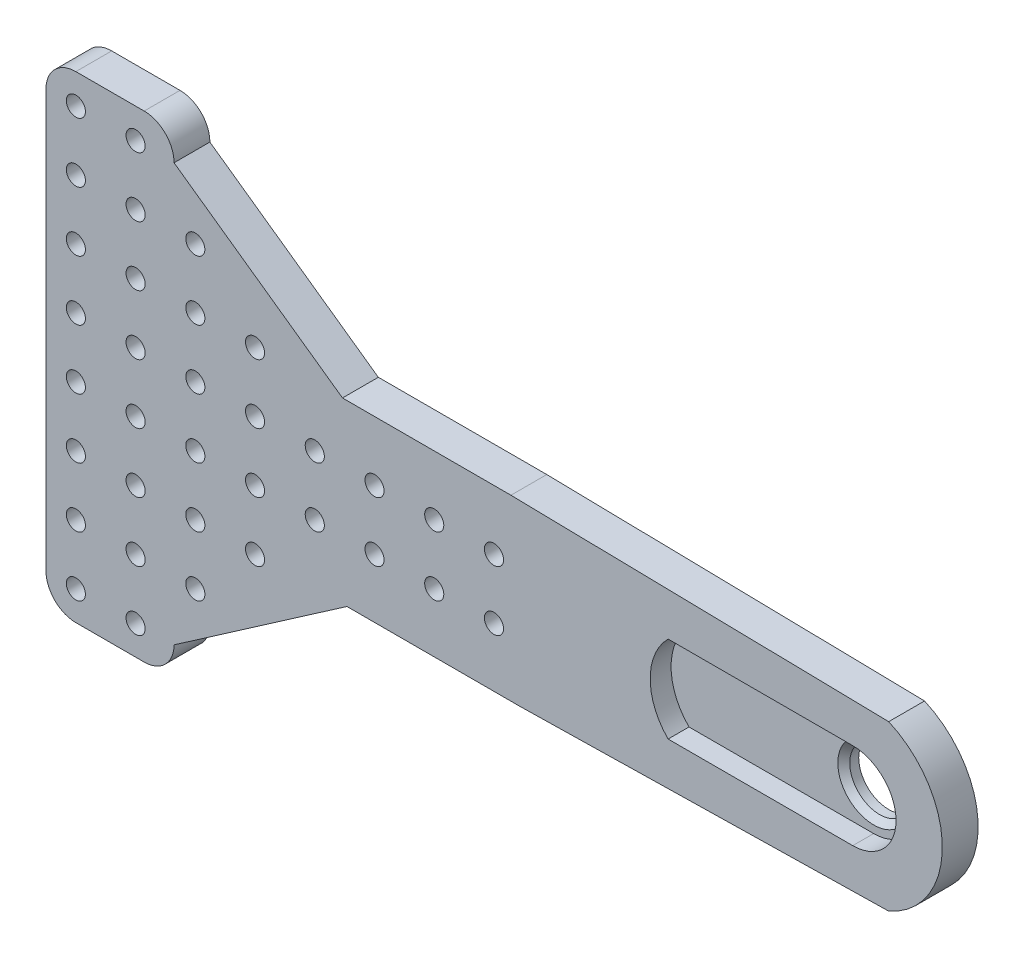
SolidWorks part; units mm, degrees
ref_plane "Ön Düzlem" through (0, 0, 0) normal (0, 0, 1) x (1, 0, 0)
ref_plane "Üst Düzlem" through (0, 0, 0) normal (0, 1, 0) x (1, 0, 0)
ref_plane "Sağ Düzlem" through (0, 0, 0) normal (1, 0, 0) x (0, 0, -1)
sketch "Çizim1" plane through (0, 0, 0) normal (0, 0, 1) x (1, 0, 0)
  line L0 (-35.653, 0) -> (24.347, 0) construction
  line L1 (-35.653, 15) -> (24.347, 15)
  line L2 (-35.653, -15) -> (24.347, -15)
  arc A0 (-35.653, 15) -> (-35.653, -15) centre (-35.653, 0) ccw
  arc A1 (24.347, -15) -> (24.347, 15) centre (24.347, 0) ccw
  point P3 (-5.653, 0)
  dimension "D1" = 15
  dimension "D2" = 60
extrude "Yükseklik-Ekstrüzyon1" add sketch "Çizim1" along normal blind 4
sketch "Çizim2" plane through (0, 0, 4) normal (0, 0, 1) x (1, 0, 0)
  line L0 (-35.653, 15) -> (-33.2438, 4.5907)
  line L1 (-33.2438, 4.5907) -> (11.7295, 15)
  line L2 (24.347, 15) -> (-35.653, 15) construction
  line L3 (11.7295, 15) -> (11.5926, 15.5911)
  line L4 (11.5926, 15.5911) -> (9.0388, 15)
  line L5 (9.0388, 15) -> (9.2838, 13.9414)
  line L6 (9.2838, 13.9414) -> (13.8573, 15)
  line L7 (13.8573, 15) -> (14.1023, 13.9414)
  line L8 (14.1023, 13.9414) -> (18.6759, 15)
  line L9 (18.6759, 15) -> (17.1385, 21.6425)
  line L10 (17.1385, 21.6425) -> (-11.5602, 15)
  line L11 (-11.5602, 15) -> (-9.1509, 4.5907)
  line L12 (-9.1509, 4.5907) -> (35.8223, 15)
  line L13 (-35.653, 0) -> (-9.6355, 0) construction
  line L14 (-9.1509, -4.5907) -> (35.8223, -15)
  line L15 (-35.653, -15) -> (24.347, -15)
  line L16 (24.347, 15) -> (-35.653, 15)
  line L17 (-35.653, -15) -> (24.347, -15)
  line L18 (35.8223, 15) -> (-35.653, 15)
  line L19 (-11.5602, -15) -> (-9.1509, -4.5907)
  line L20 (17.1385, -21.6425) -> (-11.5602, -15)
  line L21 (18.6759, -15) -> (17.1385, -21.6425)
  line L22 (14.1023, -13.9414) -> (18.6759, -15)
  line L23 (13.8573, -15) -> (14.1023, -13.9414)
  line L24 (9.2838, -13.9414) -> (13.8573, -15)
  line L25 (9.0388, -15) -> (9.2838, -13.9414)
  line L26 (11.5926, -15.5911) -> (9.0388, -15)
  line L27 (11.7295, -15) -> (11.5926, -15.5911)
  line L28 (-33.2438, -4.5907) -> (11.7295, -15)
  line L29 (-35.653, -15) -> (-33.2438, -4.5907)
  arc A2 (-35.653, 15) -> (-35.653, -15) centre (-35.653, 0) ccw
  arc A3 (24.347, -15) -> (24.347, 15) centre (24.347, 0) ccw
  arc A5 (24.347, -15) -> (24.347, 15) centre (24.347, 0) ccw
  line M7 (-35.653, -15) -> (24.347, -15)
  line M9 (24.347, 15) -> (-35.653, 15)
  dimension "D1" = 0
extrude "Kes-Ekstrüzyon1" cut sketch "Çizim2" against normal blind 4 contours L0 L1 M9 | L3 L4 M9 | L5 L6 M9 | L7 L8 M9 | L9 L10 M9 | L11 L12 M9 | L19 L17 L14 | L21 L17 L20 | L23 L17 L22 | L25 L17 L24 | L27 L17 L26 | L29 L28 M7
sketch "Çizim3" plane through (0, 0, 4) normal (0, 0, 1) x (1, 0, 0)
  circle A0 centre (24.347, 0) radius 5
  dimension "D1" = 10
extrude "Kes-Ekstrüzyon2" cut sketch "Çizim3" against normal blind 4
sketch "Çizim5" plane through (0, 0, 4) normal (0, 0, 1) x (1, 0, 0)
  line L3 (-10.376, -9.8836) -> (-11.5602, -15)
  line L4 (-11.5602, -15) -> (11.7295, -15)
  line L5 (11.7295, -15) -> (-10.376, -9.8836)
  line L6 (-10.376, -9.8836) -> (-11.5602, -15)
  line L7 (-11.5602, -15) -> (11.7295, -15)
  line L8 (11.7295, -15) -> (-10.376, -9.8836)
  line L9 (-11.5602, 15) -> (-10.376, 9.8836)
  line L10 (-10.376, 9.8836) -> (11.7295, 15)
  line L11 (11.7295, 15) -> (-11.5602, 15)
  line L12 (-11.5602, 15) -> (-10.376, 9.8836)
  line L13 (-10.376, 9.8836) -> (11.7295, 15)
  line L14 (11.7295, 15) -> (-11.5602, 15)
  dimension "D1" = 0
  dimension "D2" = 0
extrude "Kes-Ekstrüzyon3" cut sketch "Çizim5" against normal blind 4
sketch "Çizim10" plane through (0, 0, 4) normal (0, 0, 1) x (1, 0, 0)
  line L0 (23.5737, 7.2086) -> (5.173, 5.2349)
  line L1 (22.9992, -7.1236) -> (5.2458, -3.7648)
  circle A0 centre (24.347, 0) radius 7.25
  arc A1 (5.173, 5.2349) -> (5.2458, -3.7648) centre (5.2094, 0.7351) ccw
  circle M2 centre (24.347, 0) radius 5
  dimension "D1" = 14.5
  dimension "D2" = 9
extrude "Kes-Ekstrüzyon4" cut sketch "Çizim10" against normal blind 3.5 contours L0 A1 L1 A0 | A0 M2
sketch "Çizim11" plane through (0, 0, 0) normal (0, 0, -1) x (-1, 0, 0)
  line L8 (33.2438, -4.5907) -> (35.653, -15)
  line L9 (35.653, 15) -> (33.2438, 4.5907)
  line L10 (33.2438, 4.5907) -> (10.376, 9.8836)
  line L11 (10.376, 9.8836) -> (9.1509, 4.5907)
  line L12 (9.1509, 4.5907) -> (-30.3694, 13.7379)
  line L13 (-30.3694, -13.7379) -> (9.1509, -4.5907)
  line L14 (9.1509, -4.5907) -> (10.376, -9.8836)
  line L15 (10.376, -9.8836) -> (33.2438, -4.5907)
  line L16 (33.2438, -4.5907) -> (35.653, -15)
  line L17 (35.653, 15) -> (33.2438, 4.5907)
  line L18 (33.2438, 4.5907) -> (10.376, 9.8836)
  line L19 (10.376, 9.8836) -> (9.1509, 4.5907)
  line L20 (9.1509, 4.5907) -> (-30.3694, 13.7379)
  line L21 (-30.3694, -13.7379) -> (9.1509, -4.5907)
  line L22 (9.1509, -4.5907) -> (10.376, -9.8836)
  line L23 (10.376, -9.8836) -> (33.2438, -4.5907)
  circle A0 centre (-24.347, 0) radius 5 construction
  circle A1 centre (-24.347, 0) radius 5
  arc A2 (35.653, -15) -> (35.653, 15) centre (35.653, 0) ccw
  arc A3 (-30.3694, 13.7379) -> (-30.3694, -13.7379) centre (-24.347, 0) ccw
  arc A4 (35.653, -15) -> (35.653, 15) centre (35.653, 0) ccw
  arc A5 (-30.3694, 13.7379) -> (-30.3694, -13.7379) centre (-24.347, 0) ccw
  dimension "D1" = 0
extrude "Yükseklik-Ekstrüzyon3" add sketch "Çizim11" along normal blind 2
chamfer "Pah2" distance 1 angle 45 1 edges at (29.347, 0, 0.5)
sketch "Çizim12" plane through (0, 0, 4) normal (0, 0, 1) x (1, 0, 0)
  line L0 (-35.653, 15) -> (30.3694, 13.7379)
  line L1 (30.3694, -13.7379) -> (-35.653, -15)
  line L10 (-35.653, -15) -> (-33.2438, -4.5907)
  line L11 (-33.2438, -4.5907) -> (-10.376, -9.8836)
  line L12 (-10.376, -9.8836) -> (-9.1509, -4.5907)
  line L13 (-9.1509, -4.5907) -> (30.3694, -13.7379)
  line L14 (30.3694, 13.7379) -> (-9.1509, 4.5907)
  line L15 (-9.1509, 4.5907) -> (-10.376, 9.8836)
  line L16 (-10.376, 9.8836) -> (-33.2438, 4.5907)
  line L17 (-33.2438, 4.5907) -> (-35.653, 15)
  line L18 (-35.653, -15) -> (-33.2438, -4.5907)
  line L19 (-33.2438, -4.5907) -> (-10.376, -9.8836)
  line L20 (-10.376, -9.8836) -> (-9.1509, -4.5907)
  line L21 (-9.1509, -4.5907) -> (30.3694, -13.7379)
  line L22 (30.3694, 13.7379) -> (-9.1509, 4.5907)
  line L23 (-9.1509, 4.5907) -> (-10.376, 9.8836)
  line L24 (-10.376, 9.8836) -> (-33.2438, 4.5907)
  line L25 (-33.2438, 4.5907) -> (-35.653, 15)
  arc A2 (-35.653, 15) -> (-35.653, -15) centre (-35.653, 0) ccw
  arc A3 (30.3694, -13.7379) -> (30.3694, 13.7379) centre (24.347, 0) ccw
  arc A4 (-35.653, 15) -> (-35.653, -15) centre (-35.653, 0) ccw
  arc A5 (30.3694, -13.7379) -> (30.3694, 13.7379) centre (24.347, 0) ccw
  line M16 (-35.653, -15) -> (-33.2438, -4.5907)
  line M17 (-33.2438, -4.5907) -> (-10.376, -9.8836)
  line M18 (-10.376, -9.8836) -> (-9.1509, -4.5907)
  line M19 (-9.1509, -4.5907) -> (30.3694, -13.7379)
  line M21 (30.3694, 13.7379) -> (-9.1509, 4.5907)
  line M22 (-9.1509, 4.5907) -> (-10.376, 9.8836)
  line M23 (-10.376, 9.8836) -> (-33.2438, 4.5907)
  line M24 (-33.2438, 4.5907) -> (-35.653, 15)
  dimension "D1" = 0
extrude "Yükseklik-Ekstrüzyon4" add sketch "Çizim12" against normal up to surface (6 mm away) contours L0 M24 M23 M22 M21 | L1 M19 M18 M17 M16 up to face at (-12.2131, 0, -2)
sketch "Çizim13" plane through (0, 0, 4) normal (0, 0, 1) x (1, 0, 0)
  line L0 (-32.8787, 14.947) -> (-32.5322, 34.86)
  line L1 (-35.653, 15) -> (30.3694, 13.7379) construction
  line L2 (-37.5315, 39.947) -> (-45.7205, 39.947)
  line L3 (-50.7205, 34.947) -> (-50.7205, -34.9515)
  line L4 (-45.7205, -39.9515) -> (-37.8787, -39.9515)
  line L5 (-32.8787, -34.9515) -> (-32.8787, 14.947)
  line L6 (30.3694, -13.7379) -> (-35.653, -15) construction
  arc A0 (-50.7205, -34.9515) -> (-45.7205, -39.9515) centre (-45.7205, -34.9515) ccw
  arc A1 (-37.8787, -39.9515) -> (-32.8787, -34.9515) centre (-37.8787, -34.9515) ccw
  arc A2 (-32.5322, 34.86) -> (-37.5315, 39.947) centre (-37.5315, 34.947) ccw
  arc A3 (-45.7205, 39.947) -> (-50.7205, 34.947) centre (-45.7205, 34.947) ccw
  point P13 (-32.8787, -39.9515)
  point P16 (-32.4437, 39.947)
  dimension "D3" = 5
  dimension "D1" = 25
  dimension "D2" = 25
extrude "Yükseklik-Ekstrüzyon5" add sketch "Çizim13" against normal up to surface (6 mm away)
sketch "Çizim14" plane through (0, 0, 4) normal (0, 0, 1) x (1, 0, 0)
  line L0 (-50.7205, 34.947) -> (-50.7205, -34.9515) construction
  line L1 (-50.7205, 39.947) -> (-110.7205, 39.947)
  line L2 (-50.7205, 39.947) -> (-50.7205, -39.9515)
  line L3 (-50.7205, -39.9515) -> (-110.7205, -39.9515)
  line L4 (-110.7205, 39.947) -> (-110.7205, -39.9515)
  point P6 (-110.7205, 40.2083)
  point P7 (-50.7205, 39.947)
  point P8 (-50.7205, -39.9515)
  dimension "D1" = 60
extrude "Yükseklik-Ekstrüzyon6" add sketch "Çizim14" against normal up to surface (6 mm away)
sketch "Çizim15" plane through (0, 0, 4) normal (0, 0, 1) x (1, 0, 0)
  line L0 (-32.8787, 14.947) -> (-89.2832, 14.947)
  line L1 (-89.2832, 14.947) -> (-89.2832, 39.947)
  line L2 (-50.7205, 39.947) -> (-110.7205, 39.947) construction
  line L3 (-89.2832, 39.947) -> (-32.8787, 39.947)
  line L4 (-32.8787, 39.947) -> (-29.9064, 34.8143)
  line L5 (-29.9064, 34.8143) -> (-29.9064, 23.0841)
  line L6 (-29.9064, 23.0841) -> (-32.8787, 14.947)
  line L7 (-32.8787, 14.947) -> (-32.8315, 15.579)
  line L8 (-31.3926, -14.9186) -> (-31.3926, -45.9304)
  line L9 (30.3694, -13.7379) -> (-32.8787, -14.947) construction
  line L10 (-31.3926, -45.9304) -> (-93.6883, -45.9304)
  line L11 (-31.3926, -14.9186) -> (-89.2832, -14.9186)
  line L12 (-89.2832, -14.9186) -> (-89.2832, -42.8305)
  line L13 (-89.2832, -42.8305) -> (-93.6883, -45.9304)
  line M2 (-32.8787, 14.947) -> (-32.5322, 34.86)
  arc M3 (-32.5322, 34.86) -> (-37.5315, 39.947) centre (-37.5315, 34.947) ccw
  line M4 (-37.5315, 39.947) -> (-45.7205, 39.947)
  arc M5 (-45.7205, 39.947) -> (-50.7205, 34.947) centre (-45.7205, 34.947) ccw
  line M6 (-50.7205, 34.947) -> (-50.7205, 39.947)
  line M7 (-50.7205, 39.947) -> (-110.7205, 39.947)
  line M9 (-110.7205, -39.9515) -> (-50.7205, -39.9515)
  line M10 (-50.7205, -39.9515) -> (-50.7205, -34.9515)
  arc M11 (-50.7205, -34.9515) -> (-45.7205, -39.9515) centre (-45.7205, -34.9515) ccw
  line M12 (-45.7205, -39.9515) -> (-37.8787, -39.9515)
  arc M13 (-37.8787, -39.9515) -> (-32.8787, -34.9515) centre (-37.8787, -34.9515) ccw
  line M14 (-32.8787, -34.9515) -> (-32.8787, -14.947)
  line M15 (-32.8787, -14.947) -> (30.3694, -13.7379)
extrude "Kes-Ekstrüzyon5" cut sketch "Çizim15" against normal blind 11 contours L1 L0 M2 M3 M4 M5 M6 M7 | L11 L12 M9 M10 M11 M12 M13 M14 M15
fillet "Radyus1" radius 5 4 edges at (-89.2832, -39.9515, 1) (-110.7205, -39.9515, 1) (-89.2832, 39.947, 1) (-110.7205, 39.947, 1)
sketch "Çizim17" plane through (0, 0, 4) normal (0, 0, 1) x (1, 0, 0)
  line L0 (-89.2832, 34.947) -> (-61.0809, 14.947)
  line L1 (-32.8787, 14.947) -> (-89.2832, 14.947) construction
  line L2 (-61.0809, 14.947) -> (-89.2832, 14.947)
  line L3 (-89.2832, 14.947) -> (-89.2832, 34.947)
  line L4 (-89.2832, -34.9515) -> (-60.3379, -14.9186)
  line L5 (-31.3926, -14.9186) -> (-89.2832, -14.9186) construction
  line L6 (-60.3379, -14.9186) -> (-89.2832, -14.9186)
  line L7 (-89.2832, -14.9186) -> (-89.2832, -34.9515)
extrude "Yükseklik-Ekstrüzyon7" add sketch "Çizim17" against normal up to surface (6 mm away)
sketch "Çizim18" plane through (0, 0, 4) normal (0, 0, 1) x (1, 0, 0)
  line L0 (24.347, 7.25) -> (-6.5636, 7.25)
  line L1 (24.347, -7.25) -> (-6.5636, -7.25)
  line L4 (23.5737, 7.2086) -> (5.173, 5.2349)
  line L5 (5.2458, -3.7648) -> (22.9992, -7.1236)
  line L6 (23.5737, 7.2086) -> (5.173, 5.2349)
  line L7 (5.2458, -3.7648) -> (22.9992, -7.1236)
  arc A0 (22.9992, -7.1236) -> (23.5737, 7.2086) centre (24.347, 0) ccw construction
  arc A1 (22.9992, -7.1236) -> (23.5737, 7.2086) centre (24.347, 0) ccw construction
  arc A2 (-6.5636, 7.25) -> (-6.5636, -7.25) centre (0.6864, 0) ccw
  arc A5 (5.173, 5.2349) -> (5.2458, -3.7648) centre (5.2094, 0.7351) ccw
  arc A6 (22.9992, -7.1236) -> (23.5737, 7.2086) centre (24.347, 0) ccw
  arc A7 (5.173, 5.2349) -> (5.2458, -3.7648) centre (5.2094, 0.7351) ccw
  arc A8 (22.9992, -7.1236) -> (23.5737, 7.2086) centre (24.347, 0) ccw
  line M20 (5.173, 5.2349) -> (23.5737, 7.2086)
  arc M21 (23.5737, 7.2086) -> (22.9992, -7.1236) centre (24.347, 0) cw
  line M22 (22.9992, -7.1236) -> (5.2458, -3.7648)
  arc M23 (5.2458, -3.7648) -> (5.173, 5.2349) centre (5.2094, 0.7351) cw
  dimension "D1" = 0
extrude "Kes-Ekstrüzyon6" cut sketch "Çizim18" against normal up to surface (3.5 mm away) contours L0 A2 L1 M21 M22 M23 M20 up to face at (30.347, 0, 0.5)
sketch "Çizim19" plane through (0, 0, 4) normal (0, 0, 1) x (1, 0, 0)
  circle A0 centre (-105.7205, 34.947) radius 1.6
  circle A1 centre (-95.7205, 34.947) radius 1.6
  circle A8 centre (-95.7205, 24.947) radius 1.6
  circle A9 centre (-85.7205, 24.947) radius 1.6
  circle A15 centre (-95.7205, 14.947) radius 1.6
  circle A16 centre (-85.7205, 14.947) radius 1.6
  circle A17 centre (-75.7205, 14.947) radius 1.6
  circle A22 centre (-95.7205, 4.947) radius 1.6
  circle A23 centre (-85.7205, 4.947) radius 1.6
  circle A24 centre (-75.7205, 4.947) radius 1.6
  circle A25 centre (-65.7205, 4.947) radius 1.6
  circle A26 centre (-55.7205, 4.947) radius 1.6
  circle A27 centre (-45.7205, 4.947) radius 1.6
  circle A28 centre (-35.7205, 4.947) radius 1.6
  circle A29 centre (-95.7205, -5.053) radius 1.6
  circle A30 centre (-85.7205, -5.053) radius 1.6
  circle A31 centre (-75.7205, -5.053) radius 1.6
  circle A32 centre (-65.7205, -5.053) radius 1.6
  circle A33 centre (-55.7205, -5.053) radius 1.6
  circle A34 centre (-45.7205, -5.053) radius 1.6
  circle A35 centre (-35.7205, -5.053) radius 1.6
  circle A36 centre (-95.7205, -15.053) radius 1.6
  circle A37 centre (-85.7205, -15.053) radius 1.6
  circle A38 centre (-75.7205, -15.053) radius 1.6
  circle A43 centre (-95.7205, -25.053) radius 1.6
  circle A44 centre (-85.7205, -25.053) radius 1.6
  circle A50 centre (-95.7205, -35.053) radius 1.6
  circle A57 centre (-105.7205, 24.947) radius 1.6
  circle A58 centre (-105.7205, 14.947) radius 1.6
  circle A59 centre (-105.7205, 4.947) radius 1.6
  circle A60 centre (-105.7205, -5.053) radius 1.6
  circle A61 centre (-105.7205, -15.053) radius 1.6
  circle A62 centre (-105.7205, -25.053) radius 1.6
  circle A63 centre (-105.7205, -35.053) radius 1.6
  circle A64 centre (-85.7205, 34.947) radius 1.6 [skipped]
  circle A65 centre (-75.7205, 24.947) radius 1.6 [skipped]
  circle A66 centre (-75.7205, 34.947) radius 1.6 [skipped]
  circle A67 centre (-65.7205, 24.947) radius 1.6 [skipped]
  circle A68 centre (-65.7205, 34.947) radius 1.6 [skipped]
  circle A69 centre (-55.7205, 24.947) radius 1.6 [skipped]
  circle A70 centre (-35.7205, 24.947) radius 1.6 [skipped]
  circle A71 centre (-45.7205, 24.947) radius 1.6 [skipped]
  circle A72 centre (-45.7205, 34.947) radius 1.6 [skipped]
  circle A73 centre (-35.7205, 34.947) radius 1.6 [skipped]
  circle A74 centre (-45.7205, 14.947) radius 1.6 [skipped]
  circle A75 centre (-35.7205, 14.947) radius 1.6 [skipped]
  circle A76 centre (-55.7205, 14.947) radius 1.6 [skipped]
  circle A77 centre (-65.7205, 14.947) radius 1.6 [skipped]
  circle A78 centre (-55.7205, 34.947) radius 1.6 [skipped]
  circle A79 centre (-35.7205, -35.053) radius 1.6 [skipped]
  circle A80 centre (-45.7205, -35.053) radius 1.6 [skipped]
  circle A81 centre (-65.7205, -35.053) radius 1.6 [skipped]
  circle A82 centre (-55.7205, -35.053) radius 1.6 [skipped]
  circle A83 centre (-75.7205, -35.053) radius 1.6 [skipped]
  circle A84 centre (-85.7205, -35.053) radius 1.6 [skipped]
  circle A85 centre (-75.7205, -25.053) radius 1.6 [skipped]
  circle A86 centre (-65.7205, -25.053) radius 1.6 [skipped]
  circle A87 centre (-55.7205, -25.053) radius 1.6 [skipped]
  circle A88 centre (-45.7205, -25.053) radius 1.6 [skipped]
  circle A89 centre (-35.7205, -25.053) radius 1.6 [skipped]
  circle A90 centre (-35.7205, -15.053) radius 1.6 [skipped]
  circle A91 centre (-45.7205, -15.053) radius 1.6 [skipped]
  circle A92 centre (-55.7205, -15.053) radius 1.6 [skipped]
  circle A93 centre (-65.7205, -15.053) radius 1.6 [skipped]
  dimension "D1" = 3.2
  dimension "D2" = 8
  dimension "D3" = 8
extrude "Kes-Ekstrüzyon7" cut sketch "Çizim19" against normal blind 11
